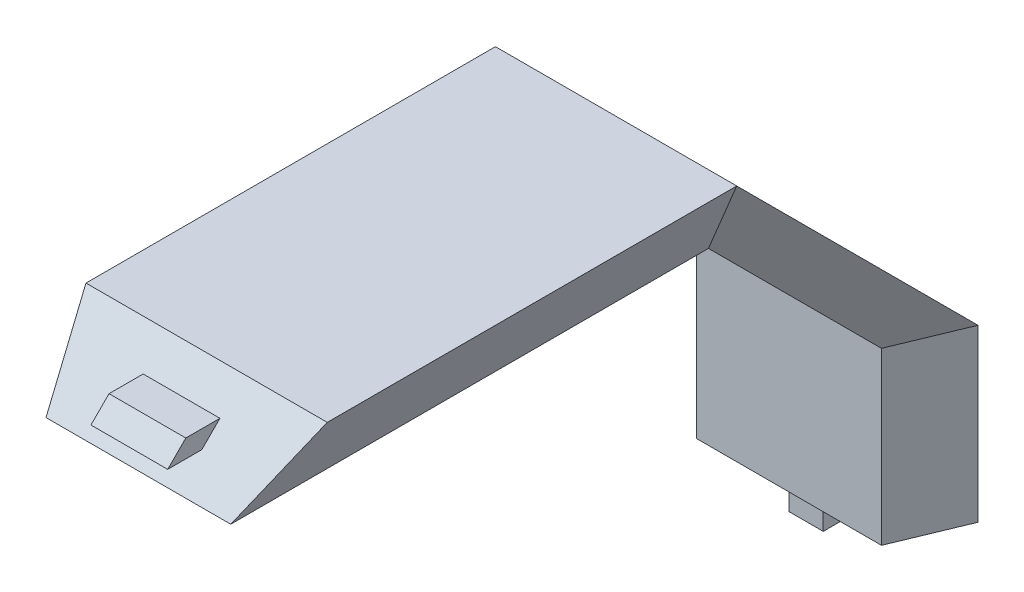
SolidWorks part; units mm, degrees
ref_plane "Front Plane" through (0, 0, 0) normal (0, 0, 1) x (1, 0, 0)
ref_plane "Top Plane" through (0, 0, 0) normal (0, 1, 0) x (1, 0, 0)
ref_plane "Right Plane" through (0, 0, 0) normal (1, 0, 0) x (0, 0, -1)
sketch "Sketch2" plane through (0, 0, 0) normal (0, 1, 0) x (1, 0, 0)
  line L0 (30.0679, 5.9006) -> (31.7248, 1.9006)
  line L1 (31.7248, 1.9006) -> (42.5532, 1.9006)
  line L2 (42.5532, 1.9006) -> (44.21, 5.9006)
  line L3 (44.21, 5.9006) -> (30.0679, 5.9006)
extrude "Boss-Extrude1" add sketch "Sketch2" along normal blind 10
ref_plane "Plane1" through (37.139, 0, 0) normal (1, 0, 0) x (0, 0, -1)
sketch "Sketch11" plane through (37.139, 0, 0) normal (1, 0, 0) x (0, 0, -1)
  line L0 (3.9006, 10) -> (-21.221, 35.1217)
  line L1 (1.9006, 10) -> (5.9006, 10) construction
  dimension "D1" = 45
sketch "Sketch9" plane through (0, 10, 0) normal (0, 1, 0) x (1, 0, 0)
  line L0 (30.0679, 5.9006) -> (31.7248, 1.9006)
  line L1 (31.7248, 1.9006) -> (42.5532, 1.9006)
  line L2 (42.5532, 1.9006) -> (44.21, 5.9006)
  line L3 (44.21, 5.9006) -> (30.0679, 5.9006)
extrude "Boss-Extrude5" add sketch "Sketch9" along direction (0, 0.7071, 0.7071) on the side of the normal blind 20
sketch "Sketch14" plane through (37.139, -13.0111, 13.0111) normal (1, 0, 0) x (0, -0.1109, -0.9938)
  line L0 (0.6181, 37.4531) -> (-3.3572, 37.0093)
  line L1 (-3.3572, 37.0093) -> (1.0619, 33.4778)
  line L2 (-3.3572, 37.0093) -> (12.2667, 24.5235) construction
  line L3 (1.0619, 33.4778) -> (0.6181, 37.4531)
  dimension "D1" = 45
extrude "Cut-Extrude1" cut sketch "Sketch14" along direction (1, 0, 0) on the side against the normal through all and the other way through all
sketch "Sketch15" plane through (0, 0, 8.2415) normal (0, 0, 1) x (1, 0, 0)
  line L0 (30.0679, 24.1421) -> (31.7248, 20.1421)
  line L1 (31.7248, 20.1421) -> (42.5532, 20.1421)
  line L2 (42.5532, 20.1421) -> (44.21, 24.1421)
  line L3 (44.21, 24.1421) -> (30.0679, 24.1421)
extrude "Boss-Extrude7" add sketch "Sketch15" along normal blind 28
sketch "Sketch30" plane through (37.139, -12.6118, 0.4451) normal (1, 0, 0) x (0, -0.0036, -1)
  line L0 (-35.9281, 36.6252) -> (-35.9138, 32.6252)
  line L1 (-35.9138, 32.6252) -> (-31.9282, 36.6395)
  line L3 (-31.9282, 36.6395) -> (-35.9281, 36.6252)
  line L7 (-35.9138, 32.6252) -> (-35.9281, 36.6252) construction
  line L8 (-35.9281, 36.6252) -> (-7.9283, 36.7257) construction
  dimension "D1" = 45
extrude "Cut-Extrude3" cut sketch "Sketch30" along direction (-1, 0, 0) on the side against the normal through all and the other way through all
sketch "Sketch31" plane through (0, 28.1918, 28.1918) normal (0, 0.7071, 0.7071) x (1, 0, 0)
  line L0 (30.0679, -5.7271) -> (44.21, -5.7271) construction
  line L1 (34.889, -7.8055) -> (39.389, -7.8055)
  line L2 (34.889, -7.8055) -> (34.889, -9.3055)
  line L3 (34.889, -9.3055) -> (39.389, -9.3055)
  line L4 (39.389, -7.8055) -> (39.389, -9.3055)
  line L5 (34.889, -7.8055) -> (39.389, -9.3055) construction
  line L6 (34.889, -9.3055) -> (39.389, -7.8055) construction
  line L7 (44.21, -5.7271) -> (42.5532, -11.384) construction
  point P0 (37.139, -8.5555)
  point P8 (37.139, -5.7271)
  point P9 (43.3816, -8.5555)
  dimension "D1" = 1.5
  dimension "D2" = 4.5
extrude "Boss-Extrude8" add sketch "Sketch31" along direction (0, 0, -1) on the side of the normal blind 2
sketch "Sketch32" plane through (0, 0, 0) normal (0, -1, 0) x (1, 0, 0)
  line L0 (31.7248, -1.9006) -> (42.5532, -1.9006) construction
  line L1 (36.139, -2.9006) -> (38.139, -2.9006)
  line L2 (36.139, -2.9006) -> (36.139, -4.9006)
  line L3 (36.139, -4.9006) -> (38.139, -4.9006)
  line L4 (38.139, -2.9006) -> (38.139, -4.9006)
  line L5 (36.139, -2.9006) -> (38.139, -4.9006) construction
  line L6 (36.139, -4.9006) -> (38.139, -2.9006) construction
  line L7 (42.5532, -1.9006) -> (44.21, -5.9006) construction
  point P0 (37.139, -3.9006)
  point P8 (37.139, -1.9006)
  point P9 (37.139, -2.9006)
  point P10 (43.3816, -3.9006)
  point P13 (38.139, -3.9006)
  dimension "D1" = 2
  dimension "D2" = 2
extrude "Boss-Extrude9" add sketch "Sketch32" along normal blind 2
